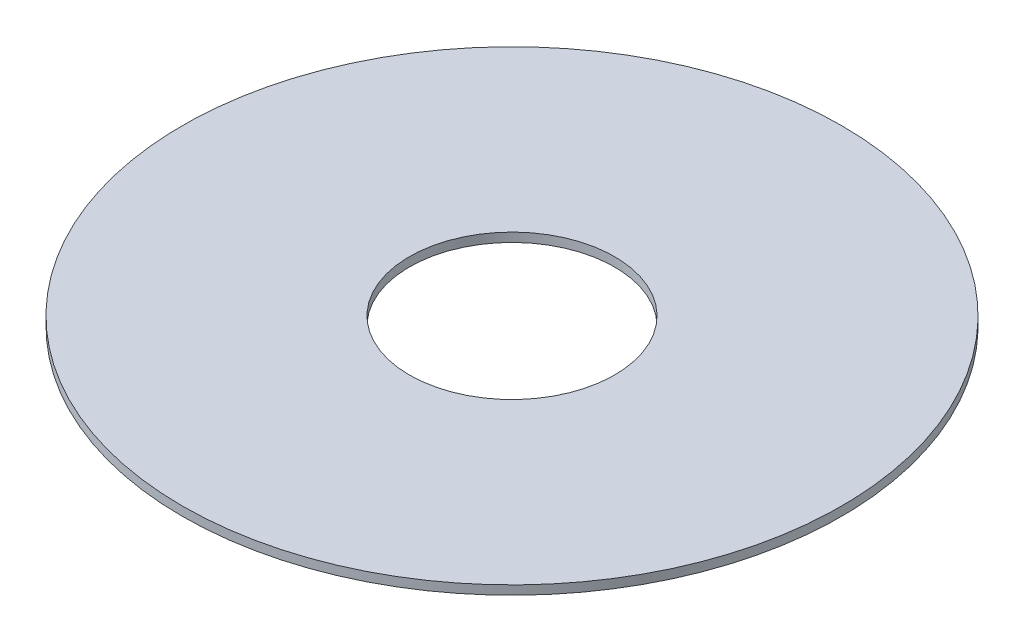
SolidWorks part; units mm, degrees
ref_plane "Front Plane" through (0, 0, 0) normal (0, 0, 1) x (1, 0, 0)
ref_plane "Top Plane" through (0, 0, 0) normal (0, 1, 0) x (1, 0, 0)
ref_plane "Right Plane" through (0, 0, 0) normal (1, 0, 0) x (0, 0, -1)
sketch "Sketch1" plane through (0, 0, 0) normal (0, 1, 0) x (1, 0, 0)
  circle A0 centre (0, 0) radius 12.85
  circle A1 centre (0, 0) radius 4
  dimension "D1" = 8
  dimension "D2" = 25.7
extrude "Boss-Extrude1" add sketch "Sketch1" along normal blind 0.35 contours A0 | A1
